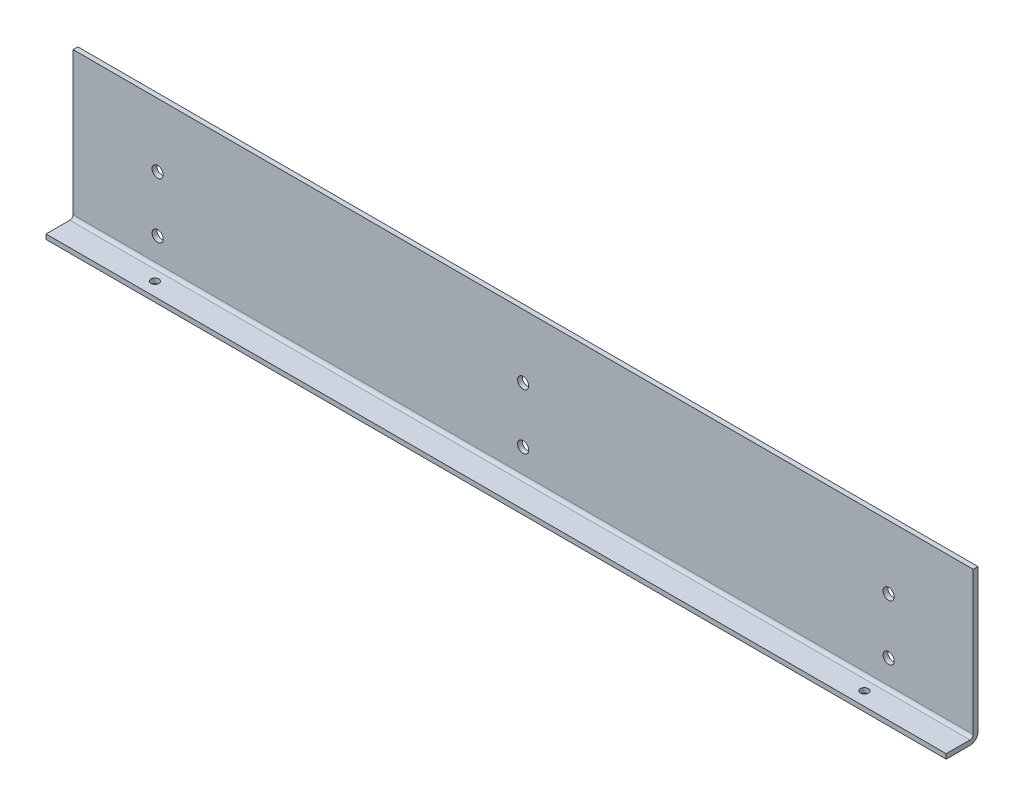
SolidWorks part; units mm, degrees
ref_plane "정면" through (0, 0, 0) normal (0, 0, 1) x (1, 0, 0)
ref_plane "윗면" through (0, 0, 0) normal (0, 1, 0) x (1, 0, 0)
ref_plane "우측면" through (0, 0, 0) normal (1, 0, 0) x (0, 0, -1)
sketch "스케치1" plane through (0, 0, 0) normal (0, 0, 1) x (1, 0, 0)
  line L1 (0, 0) -> (566.5, 0)
  line L2 (0, 0) -> (0, 95)
  line L3 (0, 95) -> (566.5, 95)
  line L4 (566.5, 0) -> (566.5, 95)
  dimension "D1" = 566.5
  dimension "D2" = 95
extrude "보스-돌출1" add sketch "스케치1" along normal blind 3
sketch "스케치2" plane through (0, 0, 3) normal (0, 0, 1) x (1, 0, 0)
  line L0 (566.5, 0) -> (566.5, 95) construction
  line L1 (0, 0) -> (566.5, 0)
  line L2 (0, 0) -> (0, 3)
  line L3 (0, 3) -> (566.5, 3)
  line L4 (566.5, 0) -> (566.5, 3)
  dimension "D1" = 3
extrude "보스-돌출2" add sketch "스케치2" along normal blind 17
sketch "스케치3" plane through (0, 0, 3) normal (0, 0, 1) x (1, 0, 0)
  line L0 (0, 95) -> (0, 3) construction
  line L1 (0, 0) -> (566.5, 0) construction
  circle A0 centre (53.25, 55) radius 3.5
  circle A1 centre (53.25, 20) radius 3.5
  circle A2 centre (283.25, 55) radius 3.5
  circle A3 centre (283.25, 20) radius 3.5
  circle A4 centre (513.25, 55) radius 3.5
  circle A5 centre (513.25, 20) radius 3.5
  point P12 (0, 0)
  point P13 (0, 0)
  point P14 (0, 0)
  point P15 (0, 0)
  point P16 (0, 0)
  dimension "D1" = 7
  dimension "D2" = 53.25
  dimension "D3" = 230
  dimension "D4" = 230
  dimension "D5" = 20
  dimension "D6" = 35
extrude "컷-돌출1" cut sketch "스케치3" against normal through all
sketch "스케치4" plane through (0, 3, 0) normal (0, 1, 0) x (1, 0, 0)
  line L0 (566.5, -20) -> (0, -20) construction
  line L1 (0, -20) -> (0, -3) construction
  circle A0 centre (60, -11.5) radius 2.5
  circle A1 centre (506.5, -11.5) radius 2.5
  point P6 (0, 0)
  dimension "D2" = 5
  dimension "D1" = 8.5
  dimension "D3" = 60
  dimension "D4" = 446.5
extrude "컷-돌출2" cut sketch "스케치4" against normal through all
fillet "필렛1" radius 5 1 edges at (283.25, 0, 0)
fillet "필렛2" radius 2 1 edges at (283.25, 3, 3)
